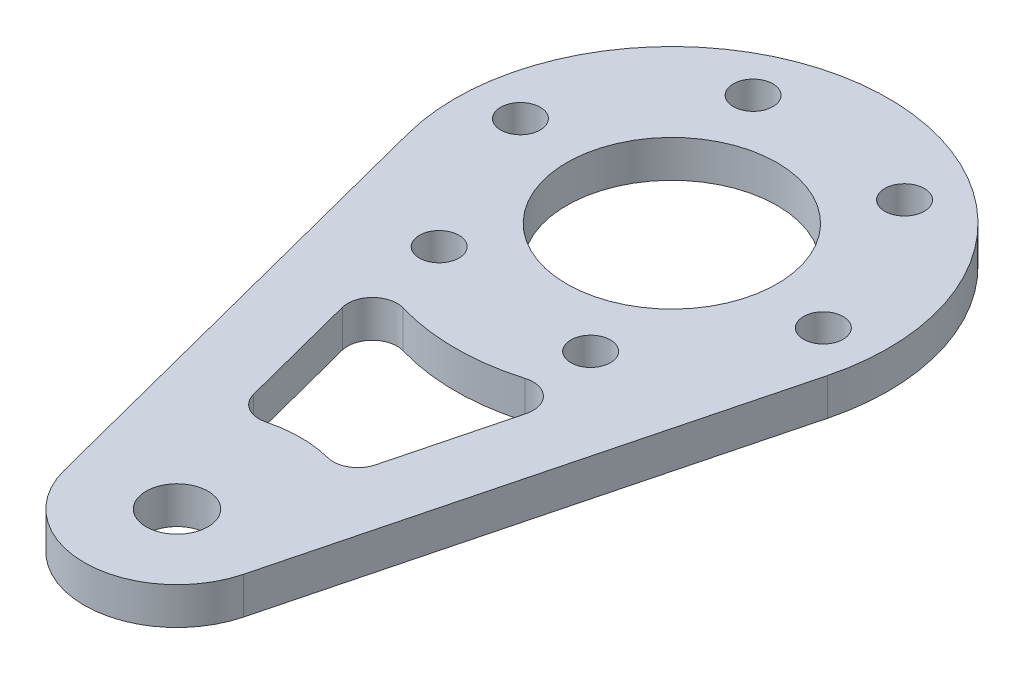
SolidWorks part; units mm, degrees
material "Thornel Mat VMA"
ref_plane "前视基准面" through (0, 0, 0) normal (0, 0, 1) x (1, 0, 0)
ref_plane "上视基准面" through (0, 0, 0) normal (0, 1, 0) x (1, 0, 0)
ref_plane "右视基准面" through (0, 0, 0) normal (1, 0, 0) x (0, 0, -1)
other "Configuration Table"
sketch "草图1" plane through (0, 0, 0) normal (0, 1, 0) x (1, 0, 0)
  line L0 (-7.2618, -41.875) -> (-16.9443, -4.375)
  line L1 (7.2618, -41.875) -> (16.9443, -4.375)
  circle A0 centre (0, 0) radius 13.5 construction
  circle A1 centre (0, -40) radius 7.5
  circle A2 centre (0, 0) radius 17.5
  circle A3 centre (0, -40) radius 2.5
  dimension "D1" = 35
  dimension "D2" = 27
  dimension "D4" = 5
  dimension "D5" = 15
  dimension "D3" = 40
extrude "凸台-拉伸1" add sketch "草图1" along normal blind 3 contours A2 | A2 L0 A1 L1 | A1 A3
sketch "草图2" plane through (0, 0, 0) normal (0, -1, 0) x (1, 0, 0)
  circle A0 centre (13.4463, 1.2033) radius 1.6
  circle A1 centre (-5.6811, -12.2465) radius 1.6
  circle A2 centre (-7.7652, 11.0432) radius 1.6
  circle A3 centre (0, 0) radius 8.5
  dimension "D1" = 3.2
  dimension "D2" = 17
extrude "切除-拉伸1" cut sketch "草图2" against normal blind 4
pattern_circular "阵列(圆周)1" count 2 over 360 about axis through (0, 0, 0) along (0, 1, 0) of "切除-拉伸1"
sketch "草图3" plane through (0, 0, 0) normal (0, -1, 0) x (1, 0, 0)
  line L0 (8.4345, 15.3333) -> (4.386, 31.0132)
  line L1 (-8.4345, 15.3333) -> (-4.386, 31.0132)
  line L2 (7.2618, 41.875) -> (16.9443, 4.375) construction
  line L3 (-7.2618, 41.875) -> (-16.9443, 4.375) construction
  circle A0 centre (0, 0) radius 17.5
  circle A1 centre (0, 40) radius 10
  point P14 (-12.1031, 23.125)
  dimension "D3" = 20
  dimension "D4" = 35
  dimension "D1" = 5.5
  dimension "D2" = 5.5
extrude "切除-拉伸2" cut sketch "草图3" against normal blind 4 contours A1 L1 A0 L0
fillet "圆角1" radius 2 4 edges at (8.4345, 1.5, 15.3333) (-8.4345, 1.5, 15.3333) (4.386, 1.5, 31.0132) (-4.386, 1.5, 31.0132)
